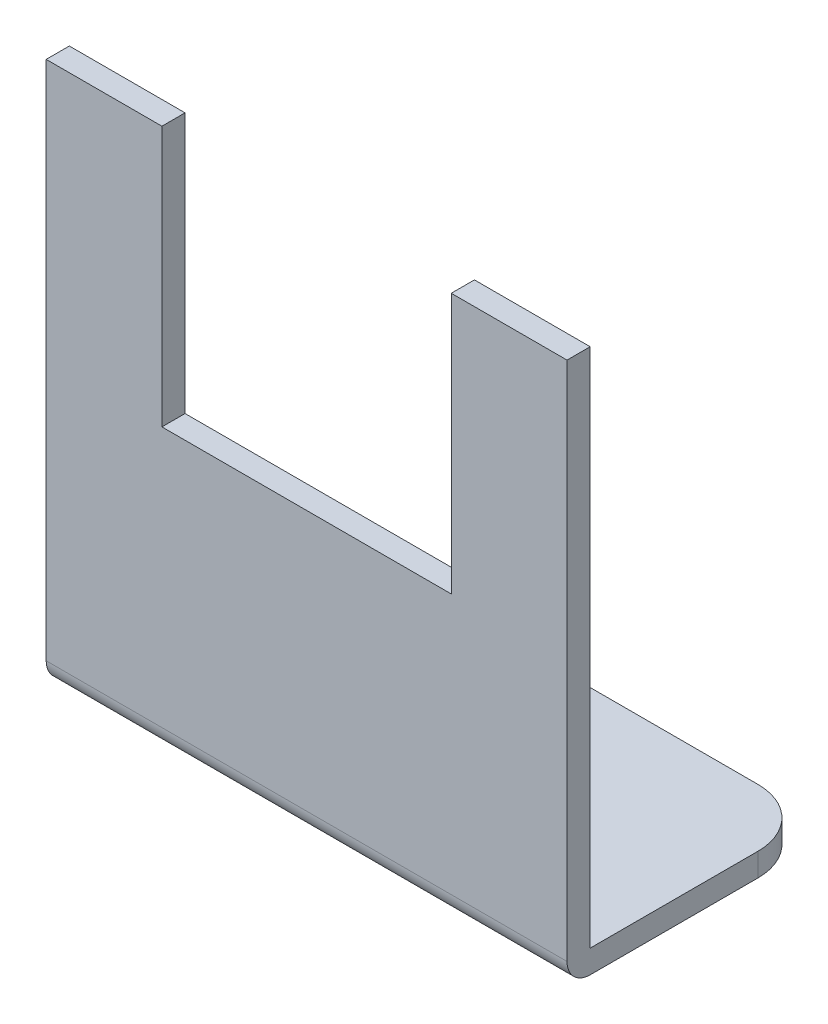
SolidWorks part; units mm, degrees
ref_plane "Front Plane" through (0, 0, 0) normal (0, 0, 1) x (1, 0, 0)
ref_plane "Top Plane" through (0, 0, 0) normal (0, 1, 0) x (1, 0, 0)
ref_plane "Right Plane" through (0, 0, 0) normal (1, 0, 0) x (0, 0, -1)
sketch "Sketch1" plane through (0, 0, 0) normal (0, 0, 1) x (1, 0, 0)
  line L1 (-22.5, 23.5) -> (22.5, 23.5)
  line L2 (-22.5, 23.5) -> (-22.5, -23.5)
  line L3 (-22.5, -23.5) -> (22.5, -23.5)
  line L4 (22.5, 23.5) -> (22.5, -23.5)
  line L5 (-22.5, 23.5) -> (22.5, -23.5) construction
  line L6 (-22.5, -23.5) -> (22.5, 23.5) construction
  point P0 (0, 0)
  dimension "D1" = 45
  dimension "D2" = 47
extrude "Boss-Extrude1" add sketch "Sketch1" along normal blind 2 contours L1 L4 L3 L2
sketch "Sketch2" plane through (0, 0, 0) normal (0, 0, -1) x (-1, 0, 0)
  line L0 (22.5, 23.5) -> (22.5, -23.5) construction
  line L1 (-22.5, -23.5) -> (22.5, -23.5)
  line L2 (-22.5, -23.5) -> (-22.5, -21.5)
  line L3 (-22.5, -21.5) -> (22.5, -21.5)
  line L4 (22.5, -23.5) -> (22.5, -21.5)
  dimension "D1" = 2
extrude "Boss-Extrude2" add sketch "Sketch2" along normal blind 19.5
fillet "Fillet1" radius 2 1 edges at (0, -23.5, 2)
fillet "Fillet2" radius 5 2 edges at (-22.5, -22.5, -19.5) (22.5, -22.5, -19.5)
sketch "Sketch3" plane through (0, 0, 2) normal (0, 0, 1) x (1, 0, 0)
  line L0 (-22.5, 23.5) -> (22.5, 23.5) construction
  line L1 (-12.5, 23.5) -> (12.5, 23.5)
  line L2 (-12.5, 23.5) -> (-12.5, 1)
  line L3 (-12.5, 1) -> (12.5, 1)
  line L4 (12.5, 23.5) -> (12.5, 1)
  point P6 (0, 23.5)
  dimension "D1" = 25
  dimension "D2" = 22.5
extrude "Cut-Extrude1" cut sketch "Sketch3" against normal through all contours L2 L3 L4 L1
sketch "Sketch4" plane through (0, -21.5, 0) normal (0, 1, 0) x (1, 0, 0)
  line L0 (-17.5, 19.5) -> (17.5, 19.5) construction
  circle A0 centre (0, 14.5) radius 1.5
  point P2 (0, 0)
  dimension "D1" = 3
  dimension "D2" = 5
extrude "Cut-Extrude2" cut sketch "Sketch4" against normal through all
equation "\"19.5.00mm\"=2"
